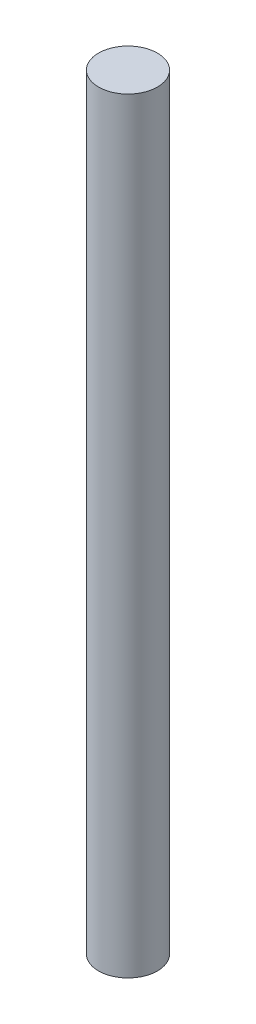
SolidWorks part; units mm, degrees
ref_plane "Front Plane" through (0, 0, 0) normal (0, 0, 1) x (1, 0, 0)
ref_plane "Top Plane" through (0, 0, 0) normal (0, 1, 0) x (1, 0, 0)
ref_plane "Right Plane" through (0, 0, 0) normal (1, 0, 0) x (0, 0, -1)
sketch "Sketch1" plane through (0, 0, 0) normal (0, 1, 0) x (1, 0, 0)
  circle A0 centre (0, 0) radius 5
extrude "Boss-Extrude1" add sketch "Sketch1" along normal blind 130
